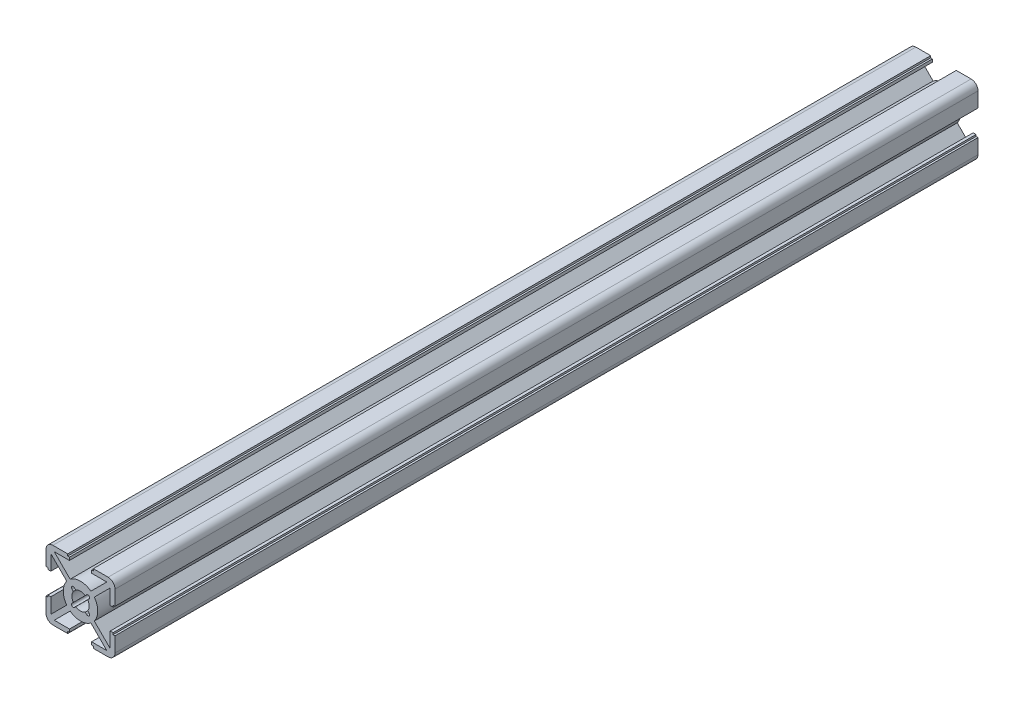
SolidWorks part; units mm, degrees
ref_plane "Ön Düzlem" through (0, 0, 0) normal (0, 0, 1) x (1, 0, 0)
ref_plane "Üst Düzlem" through (0, 0, 0) normal (0, 1, 0) x (1, 0, 0)
ref_plane "Sağ Düzlem" through (0, 0, 0) normal (1, 0, 0) x (0, 0, -1)
sketch "Çizim1" plane through (0, 0, 0) normal (0, 0, 1) x (1, 0, 0)
  line L0 (0, 13.544) -> (0, -12.4346) construction
  line L1 (0, 0) -> (-12.8733, -11.663) construction
  line L2 (15.4428, 0) -> (-17.1022, 0) construction
  line L3 (0, 0) -> (11.9441, 11.9441) construction
  line L4 (2.1213, 2.1213) -> (2.4749, 1.7678) construction
  line L5 (2.4749, 1.7678) -> (1.7678, 2.4749) construction
  line L6 (2.4749, 1.7678) -> (2.0856, 1.3785)
  line L7 (8.6, 7.6101) -> (8.6, 3.2)
  line L8 (1.3785, 2.0856) -> (1.7678, 2.4749)
  line L9 (8, 10) -> (3.7, 10)
  line L10 (3.7, 10) -> (3.7, 9.44)
  line L11 (3.7, 9.44) -> (3.2, 9.44)
  line L12 (3.2, 9.44) -> (3.2, 8.6)
  line L13 (3.0057, 3.9957) -> (7.6101, 8.6)
  line L14 (7.6101, 8.6) -> (3.2, 8.6)
  line L15 (9.44, 3.2) -> (8.6, 3.2)
  line L16 (9.44, 3.7) -> (9.44, 3.2)
  line L17 (10, 3.7) -> (9.44, 3.7)
  line L18 (10, 8) -> (10, 3.7)
  line L19 (8.6, 7.6101) -> (3.9957, 3.0057)
  line L20 (1.3785, -2.0856) -> (1.7678, -2.4749)
  line L21 (2.4749, -1.7678) -> (2.0856, -1.3785)
  line L22 (3.0057, -3.9957) -> (7.6101, -8.6)
  line L23 (3.2, -9.44) -> (3.2, -8.6)
  line L24 (3.7, -9.44) -> (3.2, -9.44)
  line L25 (3.7, -10) -> (3.7, -9.44)
  line L26 (7.6101, -8.6) -> (3.2, -8.6)
  line L27 (8, -10) -> (3.7, -10)
  line L28 (8.6, -7.6101) -> (3.9957, -3.0057)
  line L29 (8.6, -7.6101) -> (8.6, -3.2)
  line L30 (9.44, -3.2) -> (8.6, -3.2)
  line L31 (9.44, -3.7) -> (9.44, -3.2)
  line L32 (10, -3.7) -> (9.44, -3.7)
  line L33 (10, -8) -> (10, -3.7)
  line L34 (-1.3785, 2.0856) -> (-1.7678, 2.4749)
  line L35 (-2.4749, 1.7678) -> (-1.7678, 2.4749) construction
  line L36 (-2.1213, 2.1213) -> (-2.4749, 1.7678) construction
  line L37 (-10, -8) -> (-10, -3.7)
  line L38 (-10, -3.7) -> (-9.44, -3.7)
  line L39 (-9.44, -3.7) -> (-9.44, -3.2)
  line L40 (-9.44, -3.2) -> (-8.6, -3.2)
  line L41 (-8.6, -7.6101) -> (-8.6, -3.2)
  line L42 (-8.6, -7.6101) -> (-3.9957, -3.0057)
  line L43 (-8, -10) -> (-3.7, -10)
  line L44 (-7.6101, -8.6) -> (-3.2, -8.6)
  line L45 (-3.7, -10) -> (-3.7, -9.44)
  line L46 (-3.7, -9.44) -> (-3.2, -9.44)
  line L47 (-3.2, -9.44) -> (-3.2, -8.6)
  line L48 (-3.0057, -3.9957) -> (-7.6101, -8.6)
  line L49 (-2.4749, -1.7678) -> (-2.0856, -1.3785)
  line L50 (-1.3785, -2.0856) -> (-1.7678, -2.4749)
  line L51 (-8.6, 7.6101) -> (-3.9957, 3.0057)
  line L52 (-10, 8) -> (-10, 3.7)
  line L53 (-10, 3.7) -> (-9.44, 3.7)
  line L54 (-9.44, 3.7) -> (-9.44, 3.2)
  line L55 (-9.44, 3.2) -> (-8.6, 3.2)
  line L56 (-7.6101, 8.6) -> (-3.2, 8.6)
  line L57 (-3.0057, 3.9957) -> (-7.6101, 8.6)
  line L58 (-3.2, 9.44) -> (-3.2, 8.6)
  line L59 (-3.7, 9.44) -> (-3.2, 9.44)
  line L60 (-3.7, 10) -> (-3.7, 9.44)
  line L61 (-8, 10) -> (-3.7, 10)
  line L62 (-8.6, 7.6101) -> (-8.6, 3.2)
  line L63 (-2.4749, 1.7678) -> (-2.0856, 1.3785)
  arc A0 (1.3785, 2.0856) -> (-1.3785, 2.0856) centre (0, 0) ccw
  arc A1 (2.4749, 1.7678) -> (1.7678, 2.4749) centre (2.1213, 2.1213) ccw
  arc A2 (3.0057, 3.9957) -> (-3.0057, 3.9957) centre (0, 0) ccw
  arc A3 (3.9957, -3.0057) -> (3.9957, 3.0057) centre (0, 0) ccw
  arc A4 (2.0856, -1.3785) -> (2.0856, 1.3785) centre (0, 0) ccw
  arc A5 (1.3785, -2.0856) -> (-1.3785, -2.0856) centre (0, 0) cw
  arc A6 (2.4749, -1.7678) -> (1.7678, -2.4749) centre (2.1213, -2.1213) cw
  arc A7 (3.0057, -3.9957) -> (-3.0057, -3.9957) centre (0, 0) cw
  arc A8 (-2.4749, -1.7678) -> (-1.7678, -2.4749) centre (-2.1213, -2.1213) ccw
  arc A9 (-2.0856, -1.3785) -> (-2.0856, 1.3785) centre (0, 0) cw
  arc A10 (-3.9957, -3.0057) -> (-3.9957, 3.0057) centre (0, 0) cw
  arc A11 (-2.4749, 1.7678) -> (-1.7678, 2.4749) centre (-2.1213, 2.1213) cw
  arc A12 (-10, -8) -> (-8, -10) centre (-8, -8) ccw
  arc A13 (8, -10) -> (10, -8) centre (8, -8) ccw
  arc A14 (10, 8) -> (8, 10) centre (8, 8) ccw
  arc A15 (-10, 8) -> (-8, 10) centre (-8, 8) cw
  point P82 (-10, -10)
  point P85 (10, -10)
  point P88 (10, 10)
  point P91 (-10, 10)
  dimension "D1" = 5
  dimension "D3" = 1
  dimension "D6" = 10
  dimension "D8" = 2
  dimension "D2" = 45
  dimension "D4" = 0.5
  dimension "D5" = 3.2
  dimension "D7" = 0.7
  dimension "D10" = 1.4
  dimension "D12" = 0.84
extrude "Yükseklik-Ekstrüzyon1" add sketch "Çizim1" along normal blind 250
